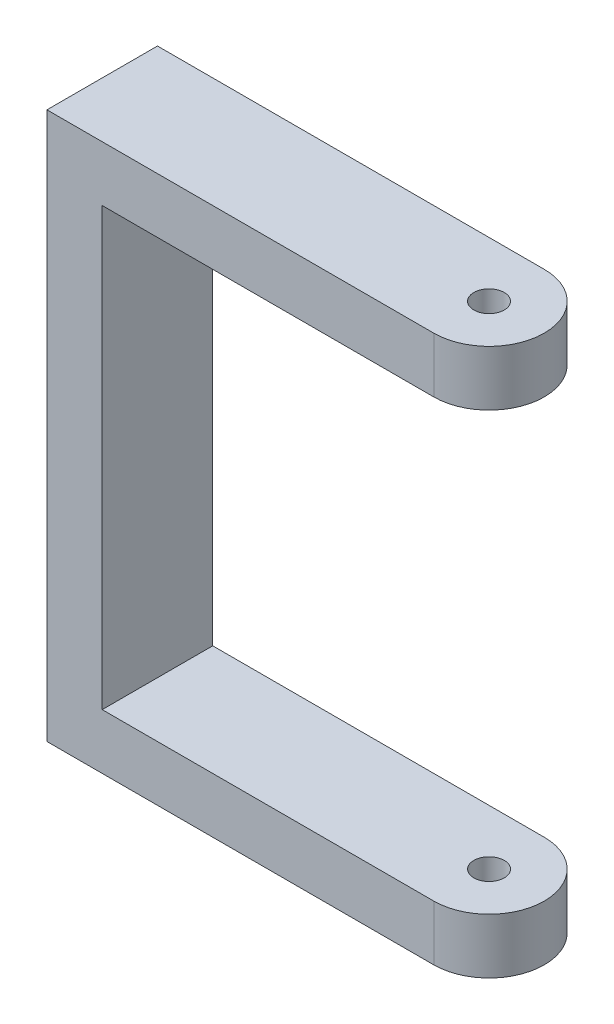
SolidWorks part; units mm, degrees
ref_plane "前视基准面" through (0, 0, 0) normal (0, 0, 1) x (1, 0, 0)
ref_plane "上视基准面" through (0, 0, 0) normal (0, 1, 0) x (1, 0, 0)
ref_plane "右视基准面" through (0, 0, 0) normal (1, 0, 0) x (0, 0, -1)
other "Configuration Table"
sketch "草图1" plane through (0, 0, 0) normal (0, 0, 1) x (1, 0, 0)
  line L0 (0, 39.5) -> (0, -39.5)
  line L1 (0, 39.5) -> (70, 39.5)
  line L2 (70, 39.5) -> (70, 49.5)
  line L3 (70, 49.5) -> (-10, 49.5)
  line L4 (-10, 49.5) -> (-10, -49.5)
  line L5 (-10, -49.5) -> (70, -49.5)
  line L6 (70, -49.5) -> (70, -39.5)
  line L7 (70, -39.5) -> (0, -39.5)
  point P4 (0, 0)
  dimension "D1" = 79
  dimension "D2" = 70
  dimension "D3" = 10
  dimension "D4" = 10
  dimension "D5" = 10
extrude "凸台-拉伸1" add sketch "草图1" along normal blind 20
sketch "草图2" plane through (0, 49.5, 0) normal (0, 1, 0) x (1, 0, 0)
  line L0 (-10, -10) -> (70, -10) construction
  line L1 (-10, -20) -> (-10, 0) construction
  line L2 (70, -20) -> (70, 0) construction
  line L3 (70, 0) -> (-10, 0) construction
  circle A0 centre (60, -10) radius 10
  circle A1 centre (60, -10) radius 2.75
  line M1 (70, 0) -> (-10, 0)
  line M3 (-10, -20) -> (70, -20)
  line M4 (70, -20) -> (70, 0)
  dimension "D1" = 5.5
extrude "切除-拉伸1" cut sketch "草图2" against normal through all contours A1 L0 | L0 A1 | A0 M4 M1 | A0 M3 M4
